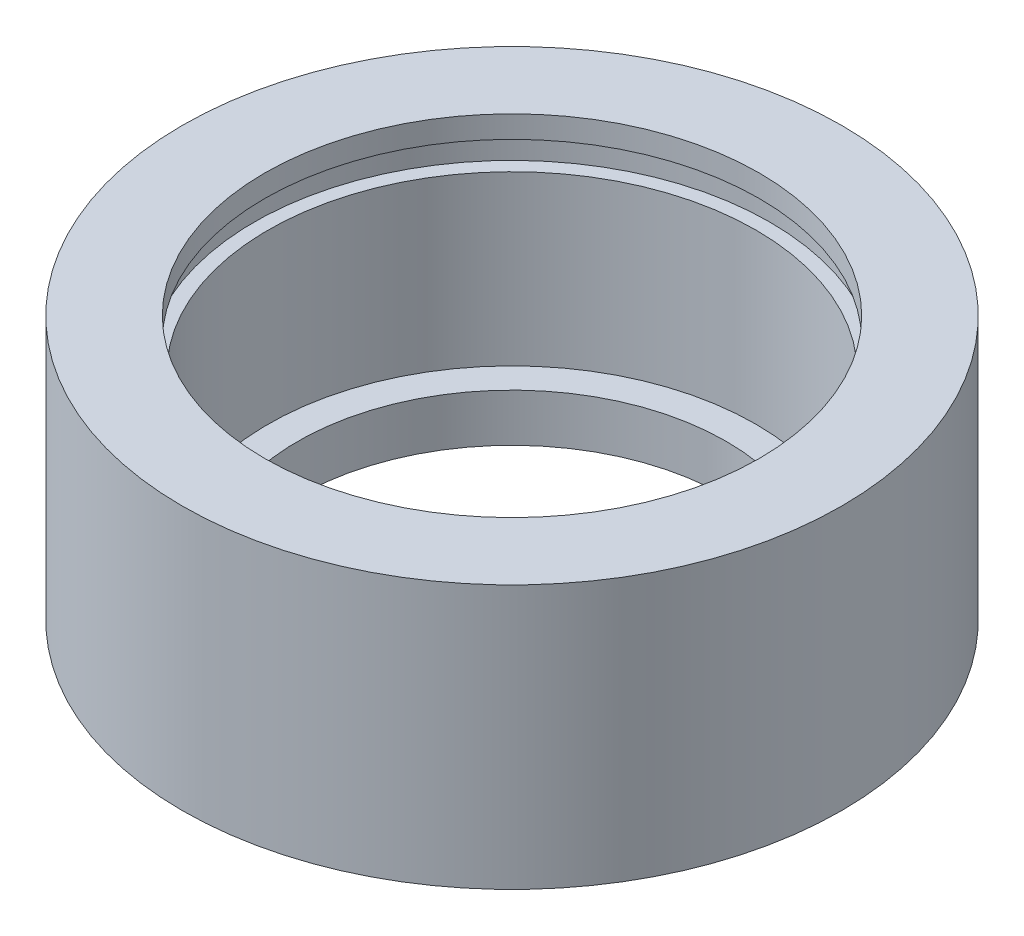
SolidWorks part; units mm, degrees
material "AISI 4130 Steel, annealed at 865C"
ref_plane "Front Plane" through (0, 0, 0) normal (0, 0, 1) x (1, 0, 0)
ref_plane "Top Plane" through (0, 0, 0) normal (0, 1, 0) x (1, 0, 0)
ref_plane "Right Plane" through (0, 0, 0) normal (1, 0, 0) x (0, 0, -1)
sketch "Sketch1" plane through (0, 0, 0) normal (0, 0, 1) x (1, 0, 0)
  line L0 (0, 0) -> (0, 8.0572) construction
  line L1 (-12.7, -5.08) -> (-8.255, -5.08)
  line L2 (-8.255, -5.08) -> (-8.255, -3.2385)
  line L3 (-8.255, -3.2385) -> (-9.398, -3.2385)
  line L4 (-9.398, -3.2385) -> (-9.398, 3.2385)
  line L5 (-9.398, 3.2385) -> (-9.9314, 3.2385)
  line L6 (-9.9314, 3.2385) -> (-9.9314, 4.2291)
  line L7 (-9.9314, 4.2291) -> (-9.525, 4.2291)
  line L8 (-9.525, 4.2291) -> (-9.525, 5.08)
  line L9 (-9.525, 5.08) -> (-12.7, 5.08)
  line L10 (-12.7, 5.08) -> (-12.7, -5.08)
  point P5 (-9.6647, 3.2385)
  dimension "D1" = 19.05
  dimension "D2" = 10.16
  dimension "D3" = 0.9906
  dimension "D4" = 6.477
  dimension "D5" = 16.51
  dimension "D6" = 18.796
  dimension "D7" = 19.8628
  dimension "D8" = 1.8415
  dimension "D9" = 25.4
  dimension "D10" = 5.08
revolve "Revolve1" add sketch "Sketch1" angle 360 about L0
ref_plane "Plane1" through (0, 0, 0) normal (0, 1, 0) x (1, 0, 0)
move or copy body "Body-Move/Copy1" [suppressed] bodies to move or copy 101
